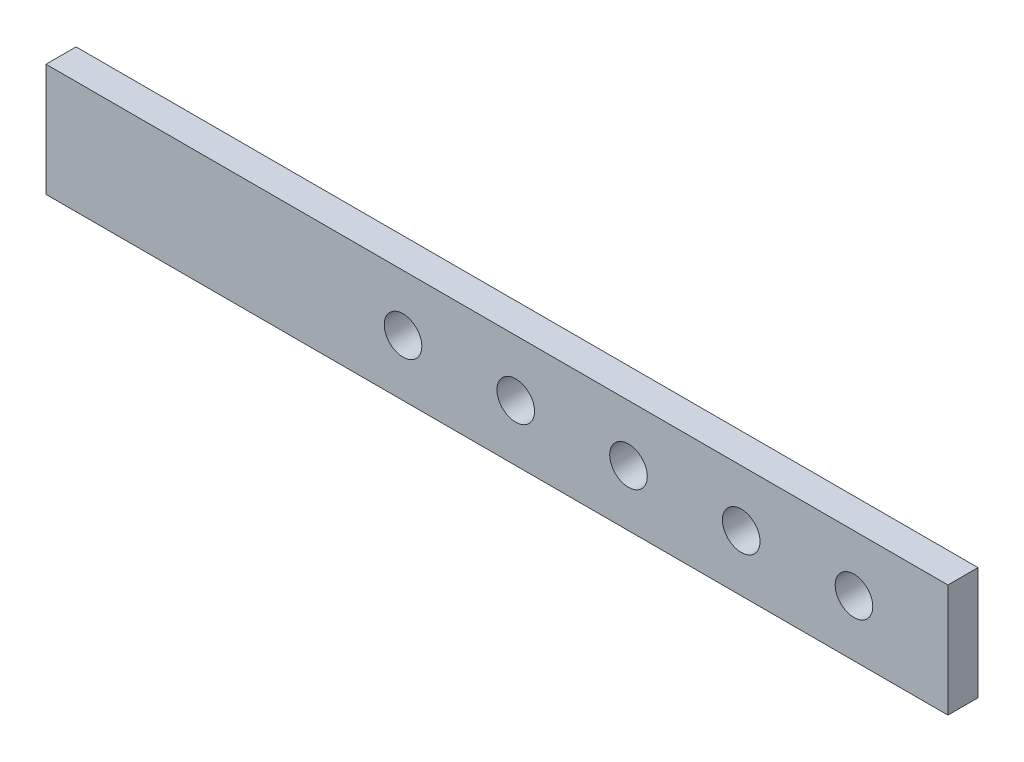
SolidWorks part; units mm, degrees
ref_plane "Front Plane" through (0, 0, 0) normal (0, 0, 1) x (1, 0, 0)
ref_plane "Top Plane" through (0, 0, 0) normal (0, 1, 0) x (1, 0, 0)
ref_plane "Right Plane" through (0, 0, 0) normal (1, 0, 0) x (0, 0, -1)
sketch "Sketch1" plane through (0, 0, 0) normal (0, 0, 1) x (1, 0, 0)
  line L1 (-174.6489, 56.2217) -> (130.1511, 56.2217)
  line L2 (-174.6489, 56.2217) -> (-174.6489, 18.1217)
  line L3 (-174.6489, 18.1217) -> (130.1511, 18.1217)
  line L4 (130.1511, 56.2217) -> (130.1511, 18.1217)
  circle A0 centre (98.4011, 37.1717) radius 6.35
  circle A1 centre (60.3011, 37.1717) radius 6.35
  circle A2 centre (22.2011, 37.1717) radius 6.35
  circle A3 centre (-15.8989, 37.1717) radius 6.35
  circle A4 centre (-53.9989, 37.1717) radius 6.35
  point P14 (130.1511, 37.1717)
  dimension "D3" = 12.7
  dimension "D9" = 12.7
  dimension "D10" = 12.7
  dimension "D11" = 12.7
  dimension "D12" = 12.7
  dimension "D1" = 304.8
  dimension "D2" = 38.1
  dimension "D4" = 31.75
  dimension "D5" = 38.1
  dimension "D6" = 38.1
  dimension "D7" = 38.1
  dimension "D8" = 38.1
extrude "Boss-Extrude1" add sketch "Sketch1" along normal blind 10.16
